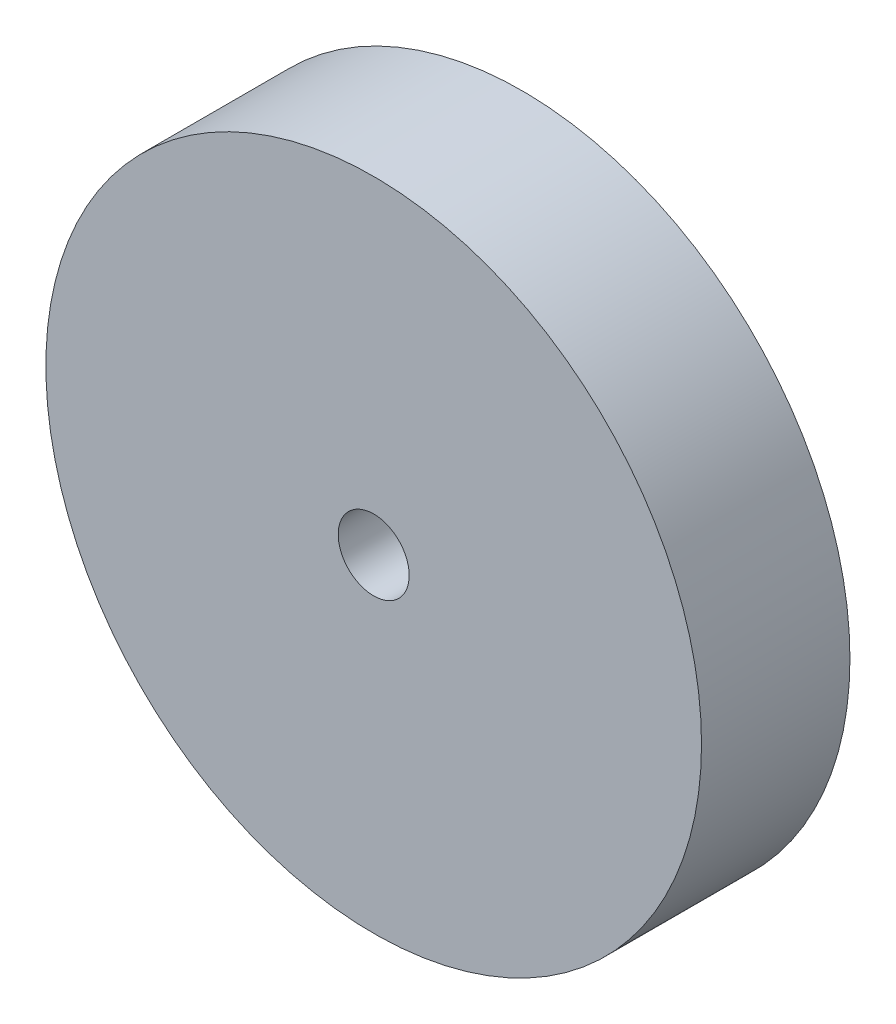
SolidWorks part; units mm, degrees
ref_plane "前视基准面" through (0, 0, 0) normal (0, 0, 1) x (1, 0, 0)
ref_plane "上视基准面" through (0, 0, 0) normal (0, 1, 0) x (1, 0, 0)
ref_plane "右视基准面" through (0, 0, 0) normal (1, 0, 0) x (0, 0, -1)
sketch "草图1" plane through (0, 0, 0) normal (0, 0, 1) x (1, 0, 0)
  circle A0 centre (0, 0) radius 50.8
  circle A1 centre (0, 0) radius 5.5
  dimension "D1" = 101.6
  dimension "D2" = 11
extrude "凸台-拉伸1" add sketch "草图1" along normal mid plane 23
